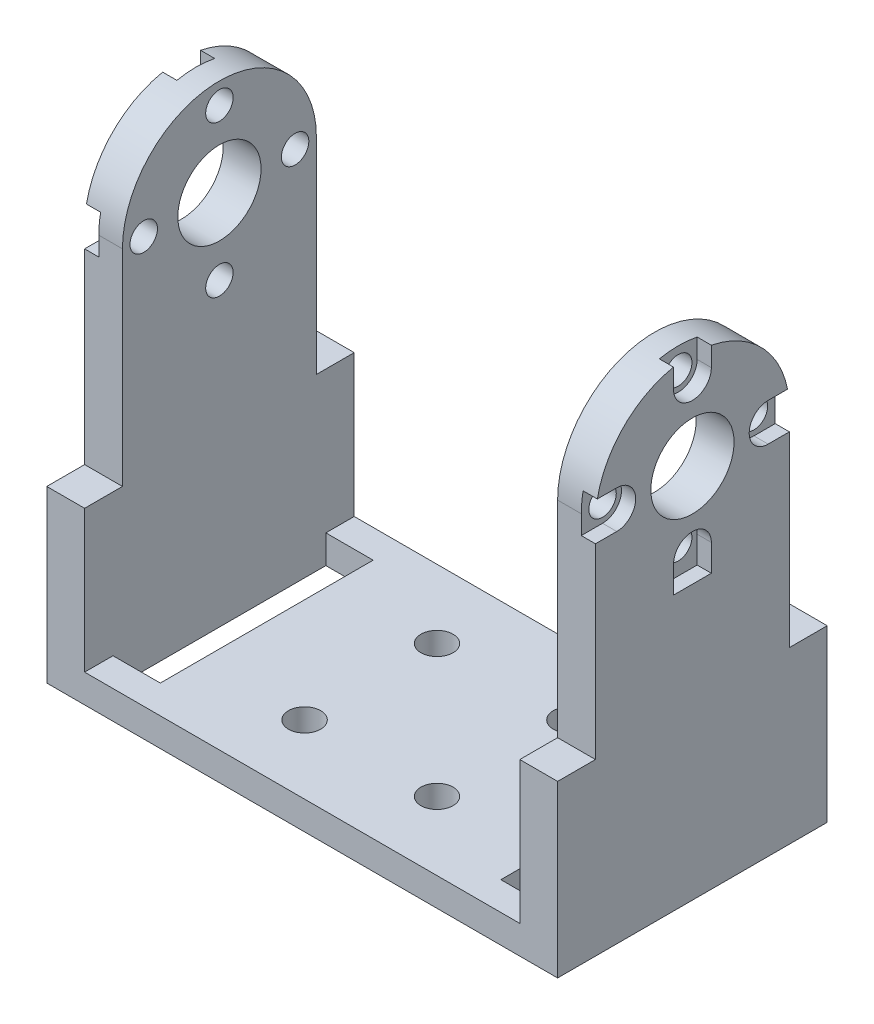
SolidWorks part; units mm, degrees
ref_plane "Front Plane" through (0, 0, 0) normal (0, 0, 1) x (1, 0, 0)
ref_plane "Top Plane" through (0, 0, 0) normal (0, 1, 0) x (1, 0, 0)
ref_plane "Right Plane" through (0, 0, 0) normal (1, 0, 0) x (0, 0, -1)
sketch "Sketch1" plane through (0, 0, 0) normal (0, 1, 0) x (1, 0, 0)
  line L0 (0, 0) -> (0, -7.6155) construction
  line L1 (-18, 14.25) -> (18, 14.25)
  line L2 (-18, 14.25) -> (-18, -14.25)
  line L3 (-18, -14.25) -> (18, -14.25)
  line L4 (18, 14.25) -> (18, -14.25)
  line L5 (0, 0) -> (0, 12.9892) construction
  line L6 (-18, 14.25) -> (-27, 14.25)
  line L7 (-18, 14.25) -> (-18, -14.25)
  line L8 (-18, -14.25) -> (-27, -14.25)
  line L9 (-27, 14.25) -> (-27, -14.25)
  line L10 (18, 14.25) -> (27, 14.25)
  line L11 (18, 14.25) -> (18, -14.25)
  line L12 (18, -14.25) -> (27, -14.25)
  line L13 (27, 14.25) -> (27, -14.25)
  line L14 (-23, 11.25) -> (-18, 11.25)
  line L15 (-23, 11.25) -> (-23, -11.25)
  line L16 (-23, -11.25) -> (-18, -11.25)
  line L17 (-18, 11.25) -> (-18, -11.25)
  line L18 (18, 11.25) -> (18, -11.25)
  line L19 (23, -11.25) -> (18, -11.25)
  line L20 (23, 11.25) -> (23, -11.25)
  line L21 (23, 11.25) -> (18, 11.25)
  circle A0 centre (0, 0) radius 7.5
  circle A1 centre (-9, 8.25) radius 1.7
  circle A2 centre (-9, -8.25) radius 1.7
  circle A3 centre (9, -8.25) radius 1.7
  circle A4 centre (9, 8.25) radius 1.7
  point P0 (0, 0)
  dimension "D3" = 9
  dimension "D4" = 8.25
  dimension "D5" = 8.25
  dimension "D6" = 9
  dimension "D7" = 9
  dimension "D9" = 15
  dimension "D14" = 3.4
  dimension "D1" = 36
  dimension "D2" = 28.5
  dimension "D8" = 9
  dimension "D10" = 4
  dimension "D11" = 3
  dimension "D12" = 3
  dimension "D13" = 5
extrude "Boss-Extrude2" add sketch "Sketch1" along normal blind 3
sketch "Sketch2" plane through (0, 3, 0) normal (0, 1, 0) x (1, 0, 0)
  line L5 (27, 14.25) -> (27, -14.25) construction
  line L6 (27, 10.25) -> (23, 10.25)
  line L7 (27, 10.25) -> (27, -10.25)
  line L8 (27, -10.25) -> (23, -10.25)
  line L9 (23, 10.25) -> (23, -10.25)
  line L10 (27, 14.25) -> (-27, 14.25) construction
  dimension "D1" = 4
  dimension "D2" = 20.5
  dimension "D3" = 4
extrude "Boss-Extrude3" add sketch "Sketch2" along normal blind 21.75
sketch "Sketch4" plane through (27, 0, 0) normal (1, 0, 0) x (0, 0, -1)
  line L0 (-10.25, 24.75) -> (10.25, 24.75) construction
  circle A0 centre (0, 24.75) radius 10.25
  point P18 (0, 17.75)
extrude "Boss-Extrude4" add sketch "Sketch4" against normal blind 4
ref_plane "Plane1" through (0, 0, 0) normal (1, 0, 0) x (0, 0, -1)
mirror "Mirror1" about plane through (0, 0, 0) normal (1, 0, 0) of "Boss-Extrude3", "Boss-Extrude4"
sketch "Sketch6" plane through (27, 0, 0) normal (1, 0, 0) x (0, 0, -1)
  line L0 (-10.25, 24.75) -> (10.25, 24.75) construction
  line L1 (0, 35) -> (0, 14.5) construction
  circle A6 centre (0, 24.75) radius 4.4
  circle A7 centre (0, 24.75) radius 8
  circle A8 centre (0, 32.75) radius 1.45
  circle A9 centre (8, 24.75) radius 1.45
  circle A10 centre (0, 16.75) radius 1.45
  circle A11 centre (-8, 24.75) radius 1.45
  circle A12 centre (0, 24.75) radius 10.25
  point P21 (0, 24.75)
  dimension "D1" = 8.8
  dimension "D2" = 16
  dimension "D3" = 4
  dimension "D4" = 2.9
extrude "Cut-Extrude3" cut sketch "Sketch6" against normal blind 4 contours A6 | A7 A11 | A7 A11 | A7 A10 | A7 A10 | A7 A9 | A7 A9 | A7 A8 | A7 A8
mirror "Mirror3" about plane through (0, 0, 0) normal (1, 0, 0) of "Cut-Extrude3"
sketch "Sketch7" plane through (27, 0, 0) normal (1, 0, 0) x (0, 0, -1)
  line L0 (10.8224, 26.75) -> (10.8224, 22.75)
  line L2 (-2, 32.75) -> (-2, 35.5724)
  line L3 (-2, 35.5724) -> (2, 35.5724)
  line L4 (2, 32.75) -> (2, 35.5724)
  line L5 (8, 22.75) -> (10.8224, 22.75)
  line L6 (8, 26.75) -> (10.8224, 26.75)
  line L7 (2, 13.9276) -> (-2, 13.9276)
  line L8 (-2, 16.75) -> (-2, 13.9276)
  line L9 (2, 16.75) -> (2, 13.9276)
  line L10 (-10.8224, 22.75) -> (-10.8224, 26.75)
  line L11 (-8, 26.75) -> (-10.8224, 26.75)
  line L12 (-8, 22.75) -> (-10.8224, 22.75)
  circle A0 centre (0, 32.75) radius 2
  circle A1 centre (0, 24.75) radius 8
  circle A2 centre (8, 24.75) radius 2
  circle A3 centre (0, 16.75) radius 2
  circle A4 centre (-8, 24.75) radius 2
  point P15 (0, 24.75)
  point P32 (0, 24.75)
  circle M1 centre (-8, 24.75) radius 1.45
  circle M2 centre (0, 16.75) radius 1.45
  circle M3 centre (8, 24.75) radius 1.45
  circle M4 centre (0, 32.75) radius 1.45
  line M6 (10.25, 3) -> (10.25, 24.75)
  arc M7 (10.25, 24.75) -> (-10.25, 24.75) centre (0, 24.75) ccw
  line M8 (-10.25, 24.75) -> (-10.25, 3)
  dimension "D1" = 4
  dimension "D3" = 4
  dimension "D2" = 4
  dimension "D4" = 4
extrude "Cut-Extrude4" cut sketch "Sketch7" against normal blind 1.5 contours A1 M1 | A1 M1 | A1 A0 M4 | A0 A1 M4 | A1 A2 M3 | A1 A2 M3 | A1 A3 M2 | A1 A3 M2 | L4 L3 L2 M7 | A0 L4 L2 M7 | A2 L5 L6 M6 M7 | A3 L8 L7 L9 | A4 L11 L12 M7 M8
mirror "Mirror4" about plane through (0, 0, 0) normal (1, 0, 0) of "Cut-Extrude4"
sketch "Sketch8" plane through (0, 3, 0) normal (0, 1, 0) x (1, 0, 0)
  line L0 (27, -14.25) -> (-27, -14.25) construction
  line L1 (-14.3907, 14.25) -> (14.3907, 14.25)
  line L2 (-14.3907, 14.25) -> (-14.3907, -14.25)
  line L3 (-14.3907, -14.25) -> (14.3907, -14.25)
  line L4 (14.3907, 14.25) -> (14.3907, -14.25)
  line L5 (-14.3907, 14.25) -> (14.3907, -14.25) construction
  line L6 (-14.3907, -14.25) -> (14.3907, 14.25) construction
  point P0 (0, 0)
extrude "Boss-Extrude5" add sketch "Sketch8" against normal blind 3
sketch "Sketch9" plane through (0, 3, 0) normal (0, 1, 0) x (1, 0, 0)
  line L3 (-7, 7) -> (7, 7)
  line L4 (-7, 7) -> (-7, -7)
  line L5 (-7, -7) -> (7, -7)
  line L6 (7, 7) -> (7, -7)
  line L7 (-7, 7) -> (7, -7) construction
  line L8 (-7, -7) -> (7, 7) construction
  circle A0 centre (0, 0) radius 5
  circle A2 centre (-7, 7) radius 1.7
  circle A3 centre (7, 7) radius 1.7
  circle A4 centre (7, -7) radius 1.7
  circle A5 centre (-7, -7) radius 1.7
  dimension "D1" = 14
  dimension "D2" = 14
  dimension "D3" = 10
  dimension "D4" = 3.4
  dimension "D5" = 2
  dimension "D6" = 2
extrude "Cut-Extrude5" cut sketch "Sketch9" against normal blind 3 contours L4 A5 L5 | L5 A4 L6 | L6 A3 L3 | L3 A3 L6 | L5 A5 L4 | L6 A4 L5 | A2
sketch "Sketch10" plane through (0, 0, 0) normal (0, -1, 0) x (1, 0, 0)
  line L1 (-27, 14.25) -> (27, 14.25)
  line L2 (-27, 14.25) -> (-27, -14.25)
  line L3 (-27, -14.25) -> (27, -14.25)
  line L4 (27, 14.25) -> (27, -14.25)
  line L5 (-23, 11.25) -> (-18, 11.25)
  line L6 (-23, 11.25) -> (-23, -11.25)
  line L7 (-23, -11.25) -> (-18, -11.25)
  line L8 (-18, 11.25) -> (-18, -11.25)
  line L9 (18, 11.25) -> (23, 11.25)
  line L10 (18, 11.25) -> (18, -11.25)
  line L11 (18, -11.25) -> (23, -11.25)
  line L12 (23, 11.25) -> (23, -11.25)
  circle A0 centre (-7, 7) radius 1.7
  circle A1 centre (-7, -7) radius 1.7
  circle A2 centre (7, -7) radius 1.7
  circle A3 centre (7, 7) radius 1.7
extrude "Boss-Extrude6" add sketch "Sketch10" along normal blind 15
sketch "Sketch11" plane through (0, 0, 14.25) normal (0, 0, 1) x (1, 0, 0)
  line L0 (23, 3) -> (23, -15) construction
  line L1 (-23, 3) -> (23, 3)
  line L2 (-23, 3) -> (-23, -12)
  line L3 (-23, -12) -> (23, -12)
  line L4 (23, 3) -> (23, -12)
  line L5 (27, -15) -> (-27, -15) construction
  dimension "D1" = 3
extrude "Cut-Extrude6" cut sketch "Sketch11" against normal through all
